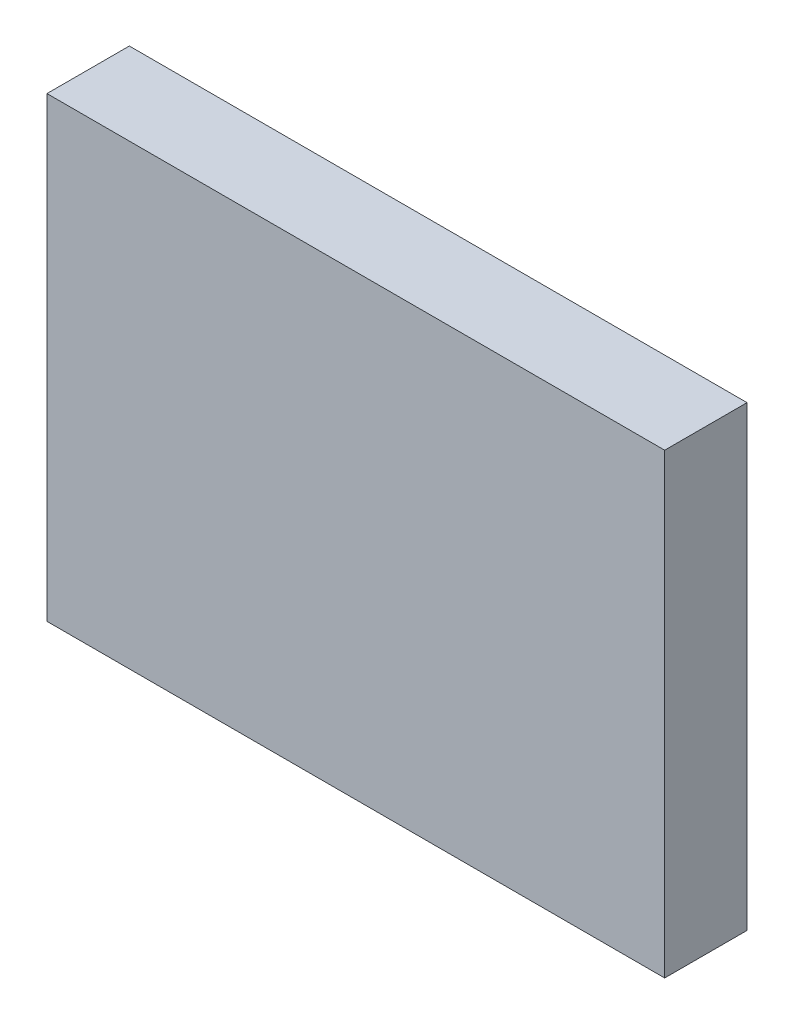
SolidWorks part; units mm, degrees
ref_plane "Alzado" through (0, 0, 0) normal (0, 0, 1) x (1, 0, 0)
ref_plane "Planta" through (0, 0, 0) normal (0, 1, 0) x (1, 0, 0)
ref_plane "Vista lateral" through (0, 0, 0) normal (1, 0, 0) x (0, 0, -1)
sketch "Croquis1" plane through (0, 0, 0) normal (0, 0, 1) x (1, 0, 0)
  line L0 (-74.7911, 45.2447) -> (-74.7911, -65.7553)
  line L1 (-74.7911, -65.7553) -> (75.2089, -65.7553)
  line L2 (75.2089, -65.7553) -> (75.2089, 45.2447)
  line L3 (75.2089, 45.2447) -> (-74.7911, 45.2447)
  dimension "D1" = 150
  dimension "D2" = 111
extrude "Saliente-Extruir1" add sketch "Croquis1" along normal blind 20
